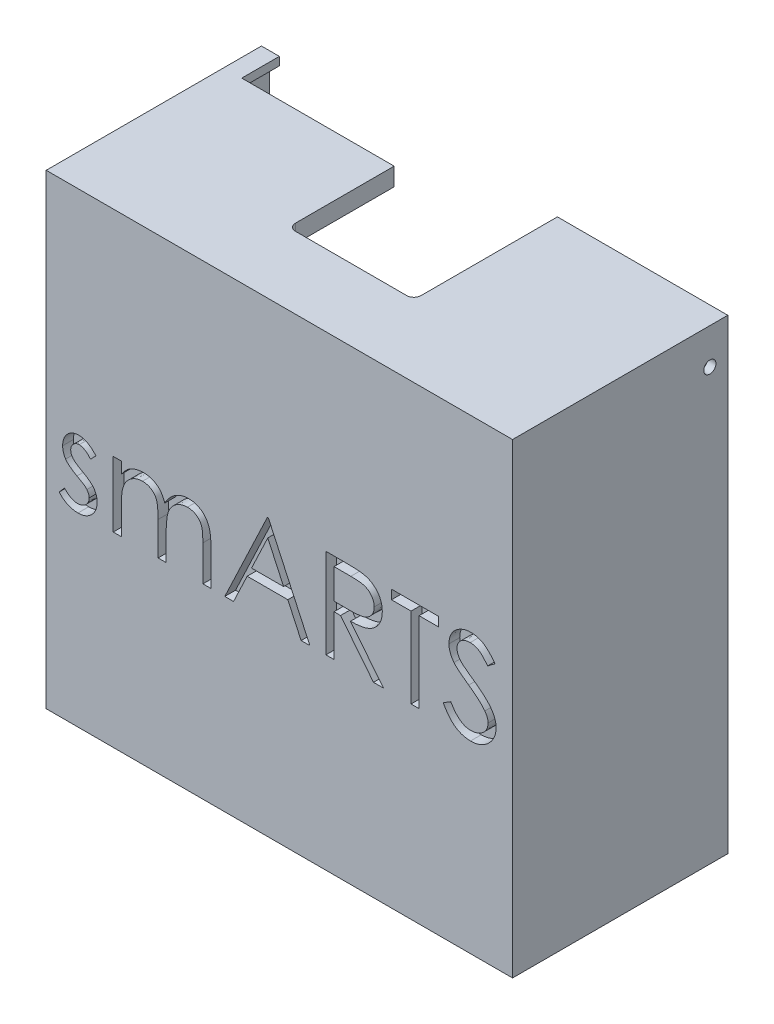
SolidWorks part; units mm, degrees
ref_plane "Alzado" through (0, 0, 0) normal (0, 0, 1) x (1, 0, 0)
ref_plane "Planta" through (0, 0, 0) normal (0, 1, 0) x (1, 0, 0)
ref_plane "Vista lateral" through (0, 0, 0) normal (1, 0, 0) x (0, 0, -1)
sketch "Croquis1" plane through (0, 0, 0) normal (0, 0, 1) x (1, 0, 0)
  line L1 (-65, -65) -> (65, -65)
  line L2 (-65, -65) -> (-65, 65)
  line L3 (-65, 65) -> (65, 65)
  line L4 (65, -65) -> (65, 65)
  line L5 (-65, -65) -> (65, 65) construction
  line L6 (-65, 65) -> (65, -65) construction
  point P0 (0, 0)
  dimension "D1" = 130
  dimension "D2" = 130
extrude "Saliente-Extruir1" add sketch "Croquis1" along normal blind 60
sketch "Croquis2" plane through (0, 0, 0) normal (0, 0, -1) x (-1, 0, 0)
  line L1 (-62.7, -62.7) -> (62.7, -62.7)
  line L2 (-62.7, -62.7) -> (-62.7, 62.7)
  line L3 (-62.7, 62.7) -> (62.7, 62.7)
  line L4 (62.7, -62.7) -> (62.7, 62.7)
  line L5 (-62.7, -62.7) -> (62.7, 62.7) construction
  line L6 (-62.7, 62.7) -> (62.7, -62.7) construction
  point P0 (0, 0)
  dimension "D1" = 125.4
  dimension "D2" = 125.4
extrude "Cortar-Extruir1" cut sketch "Croquis2" against normal blind 10.4
sketch "Croquis3" plane through (0, 0, 10.4) normal (0, 0, -1) x (-1, 0, 0)
  line L1 (-60, -60) -> (60, -60)
  line L2 (-60, -60) -> (-60, 60)
  line L3 (-60, 60) -> (60, 60)
  line L4 (60, -60) -> (60, 60)
  line L5 (-60, -60) -> (60, 60) construction
  line L6 (-60, 60) -> (60, -60) construction
  point P0 (0, 0)
  dimension "D1" = 120
  dimension "D2" = 120
extrude "Cortar-Extruir2" cut sketch "Croquis3" against normal blind 45
sketch "Croquis4" plane through (0, 0, 60) normal (0, 0, 1) x (1, 0, 0)
  line L0 (-65, -13) -> (65, -13) construction
  line L1 (-65, 65) -> (-65, -65) construction
  line L2 (65, -65) -> (65, 65) construction
  line L3 (-65, -65) -> (65, -65) construction
  text T0 "smARTS" font "Century Gothic" height 25
  dimension "D1" = 52
extrude "Cortar-Extruir3" cut sketch "Croquis4" against normal blind 3
sketch "Croquis5" plane through (65, 0, 0) normal (1, 0, 0) x (0, 0, -1)
  line L0 (0, -65) -> (0, 65) construction
  line L1 (-60, 65) -> (0, 65) construction
  circle A0 centre (-5, 55) radius 1.7
  dimension "D1" = 3.4
  dimension "D2" = 5
  dimension "D3" = 10
extrude "Cortar-Extruir4" cut sketch "Croquis5" against normal through all
sketch "Croquis6" plane through (0, 60, 0) normal (0, -1, 0) x (1, 0, 0)
  line L0 (60, 55.4) -> (60, 10.4) construction
  line L1 (17.5, 40) -> (-17.5, 40)
  line L2 (17.5, 40) -> (17.5, 0)
  line L3 (17.5, 0) -> (-17.5, 0)
  line L4 (-17.5, 40) -> (-17.5, 0)
  line L5 (17.5, 40) -> (-17.5, 0) construction
  line L6 (17.5, 0) -> (-17.5, 40) construction
  line L7 (65, 0) -> (-65, 0) construction
  point P0 (0, 20)
  dimension "D1" = 35
  dimension "D2" = 40
  dimension "D3" = 42.5
  dimension "D4" = 0
extrude "Cortar-Extruir6" cut sketch "Croquis6" against normal up to next
fillet "Redondeo1" radius 2 2 edges at (-17.5, 62.5, 40) (17.5, 62.5, 40)
sketch "Croquis7" plane through (0, 65, 0) normal (0, 1, 0) x (1, 0, 0)
  line L0 (65, 0) -> (17.5, 0) construction
  line L1 (17.5, 0) -> (-60, 0)
  line L2 (17.5, 0) -> (17.5, -10.5)
  line L3 (17.5, -10.5) -> (-60, -10.5)
  line L4 (-60, 0) -> (-60, -10.5)
  line L6 (-60, -55.4) -> (-60, -10.4) construction
  line L7 (17.5, -38) -> (17.5, 0) construction
  dimension "D1" = 0
  dimension "D2" = 0
  dimension "D3" = 10.5
extrude "Cortar-Extruir7" cut sketch "Croquis7" against normal up to next
